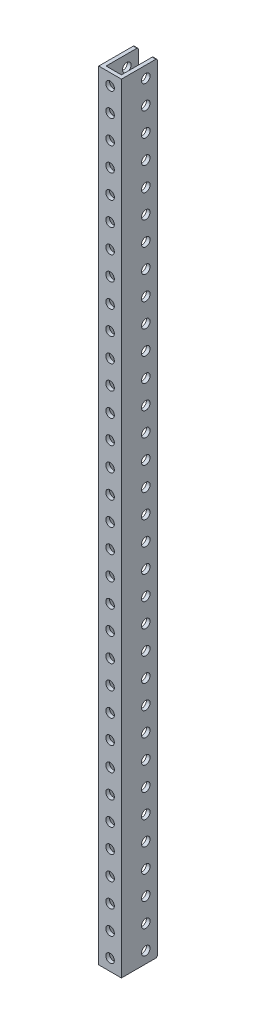
SolidWorks part; units mm, degrees
ref_plane "Front Plane" through (0, 0, 0) normal (0, 0, 1) x (1, 0, 0)
ref_plane "Top Plane" through (0, 0, 0) normal (0, 1, 0) x (1, 0, 0)
ref_plane "Right Plane" through (0, 0, 0) normal (1, 0, 0) x (0, 0, -1)
ref_plane "Plane1" through (-4.699, 0, 0) normal (-1, 0, 0) x (0, -1, 0)
sketch "Sketch1" plane through (-4.699, 0, 0) normal (-1, 0, 0) x (0, -1, 0)
  line L0 (-322.453, -13.335) -> (0, -13.335)
  line L1 (0, -13.335) -> (0, 1.524)
  line L2 (0, 1.524) -> (-322.453, 1.524)
  line L3 (-322.453, 1.524) -> (-322.453, -13.335)
extrude "Boss-Extrude1" add sketch "Sketch1" against normal blind 9.398
sketch "Sketch2" plane through (0, 0, 0) normal (0, -1, 0) x (1, 0, 0)
  line L0 (-3.175, -13.335) -> (3.175, -13.335)
  line L1 (3.175, -13.335) -> (3.175, 0)
  line L2 (3.175, 0) -> (-3.175, 0)
  line L3 (-3.175, 0) -> (-3.175, -13.335)
extrude "Cut-Extrude1" cut sketch "Sketch2" against normal through all
hole_wizard "#5 Clearance Hole1" positions "Sketch4" profile "Sketch3" hole size "#5" standard "ANSI Inch"
sketch "Sketch4" plane through (4.699, 0, 0) normal (1, 0, 0) x (0, 0, -1)
  point P0 (8.5725, 307.9115)
  point P1 (8.5725, 317.6905)
  point P2 (8.5725, 298.1325)
  point P3 (8.5725, 288.3535)
  point P4 (8.5725, 278.5745)
  point P5 (8.5725, 268.7955)
  point P6 (8.5725, 259.0165)
  point P7 (8.5725, 249.2375)
  point P8 (8.5725, 239.4585)
  point P9 (8.5725, 229.6795)
  point P10 (8.5725, 219.9005)
  point P11 (8.5725, 210.1215)
  point P12 (8.5725, 200.3425)
  point P13 (8.5725, 190.5635)
  point P14 (8.5725, 180.7845)
  point P15 (8.5725, 171.0055)
  point P16 (8.5725, 161.2265)
  point P17 (8.5725, 151.4475)
  point P18 (8.5725, 141.6685)
  point P19 (8.5725, 131.8895)
  point P20 (8.5725, 122.1105)
  point P21 (8.5725, 112.3315)
  point P22 (8.5725, 102.5525)
  point P23 (8.5725, 92.7735)
  point P24 (8.5725, 82.9945)
  point P25 (8.5725, 73.2155)
  point P26 (8.5725, 63.4365)
  point P27 (8.5725, 53.6575)
  point P28 (8.5725, 43.8785)
  point P29 (8.5725, 34.0995)
  point P30 (8.5725, 24.3205)
  point P31 (8.5725, 14.5415)
  point P32 (8.5725, 4.7625)
sketch "Sketch3" plane through (4.699, 307.9115, -8.5725) normal (0, 1, 0) x (0, 0, -1)
  line L0 (0, 0) -> (0, 1.524)
  line L1 (0, 1.524) -> (1.778, 1.524)
  line L2 (1.778, 1.524) -> (1.778, 0)
  line L5 (1.778, 0) -> (0, 0)
  line L11 (0, -6.35) -> (0, 107.95) construction
  dimension "Thru Hole Dia." = 3.556
  dimension "Thru Hole Depth" = 1.524
hole_wizard "#5 Clearance Hole2" positions "Sketch6" profile "Sketch5" hole size "#5" standard "ANSI Inch"
sketch "Sketch6" plane through (0, 0, 1.524) normal (0, 0, 1) x (1, 0, 0)
  point P0 (0, 307.9115)
  point P1 (0, 317.6905)
  point P2 (0, 298.1325)
  point P3 (0, 288.3535)
  point P4 (0, 278.5745)
  point P5 (0, 268.7955)
  point P6 (0, 259.0165)
  point P7 (0, 249.2375)
  point P8 (0, 239.4585)
  point P9 (0, 229.6795)
  point P10 (0, 219.9005)
  point P11 (0, 210.1215)
  point P12 (0, 200.3425)
  point P13 (0, 190.5635)
  point P14 (0, 180.7845)
  point P15 (0, 171.0055)
  point P16 (0, 161.2265)
  point P17 (0, 151.4475)
  point P18 (0, 141.6685)
  point P19 (0, 131.8895)
  point P20 (0, 122.1105)
  point P21 (0, 112.3315)
  point P22 (0, 102.5525)
  point P23 (0, 92.7735)
  point P24 (0, 82.9945)
  point P25 (0, 73.2155)
  point P26 (0, 63.4365)
  point P27 (0, 53.6575)
  point P28 (0, 43.8785)
  point P29 (0, 34.0995)
  point P30 (0, 24.3205)
  point P31 (0, 14.5415)
  point P32 (0, 4.7625)
sketch "Sketch5" plane through (0, 307.9115, 1.524) normal (1, 0, 0) x (0, -1, 0)
  line L0 (0, 0) -> (0, 14.859)
  line L1 (0, 14.859) -> (1.778, 14.859)
  line L2 (1.778, 14.859) -> (1.778, 0)
  line L5 (1.778, 0) -> (0, 0)
  line L11 (0, -6.35) -> (0, 107.95) construction
  dimension "Thru Hole Dia." = 3.556
  dimension "Thru Hole Depth" = 14.859
hole_wizard "#5 Clearance Hole3" positions "Sketch8" profile "Sketch7" hole size "#5" standard "ANSI Inch"
sketch "Sketch8" plane through (-3.175, 0, 0) normal (1, 0, 0) x (0, 0, -1)
  point P0 (8.5725, 307.9115)
  point P1 (8.5725, 317.6905)
  point P2 (8.5725, 298.1325)
  point P3 (8.5725, 288.3535)
  point P4 (8.5725, 278.5745)
  point P5 (8.5725, 268.7955)
  point P6 (8.5725, 259.0165)
  point P7 (8.5725, 249.2375)
  point P8 (8.5725, 239.4585)
  point P9 (8.5725, 229.6795)
  point P10 (8.5725, 219.9005)
  point P11 (8.5725, 210.1215)
  point P12 (8.5725, 200.3425)
  point P13 (8.5725, 190.5635)
  point P14 (8.5725, 180.7845)
  point P15 (8.5725, 171.0055)
  point P16 (8.5725, 161.2265)
  point P17 (8.5725, 151.4475)
  point P18 (8.5725, 141.6685)
  point P19 (8.5725, 131.8895)
  point P20 (8.5725, 122.1105)
  point P21 (8.5725, 112.3315)
  point P22 (8.5725, 102.5525)
  point P23 (8.5725, 92.7735)
  point P24 (8.5725, 82.9945)
  point P25 (8.5725, 73.2155)
  point P26 (8.5725, 63.4365)
  point P27 (8.5725, 53.6575)
  point P28 (8.5725, 43.8785)
  point P29 (8.5725, 34.0995)
  point P30 (8.5725, 24.3205)
  point P31 (8.5725, 14.5415)
  point P32 (8.5725, 4.7625)
sketch "Sketch7" plane through (-3.175, 307.9115, -8.5725) normal (0, 1, 0) x (0, 0, -1)
  line L0 (0, 0) -> (0, 1.524)
  line L1 (0, 1.524) -> (1.778, 1.524)
  line L2 (1.778, 1.524) -> (1.778, 0)
  line L5 (1.778, 0) -> (0, 0)
  line L11 (0, -6.35) -> (0, 107.95) construction
  dimension "Thru Hole Dia." = 3.556
  dimension "Thru Hole Depth" = 1.524
fillet "Fillet1" radius 0.635 4 edges at (3.937, 0, -13.335) (3.937, 322.453, -13.335) (-3.937, 322.453, -13.335) (-3.937, 0, -13.335)
